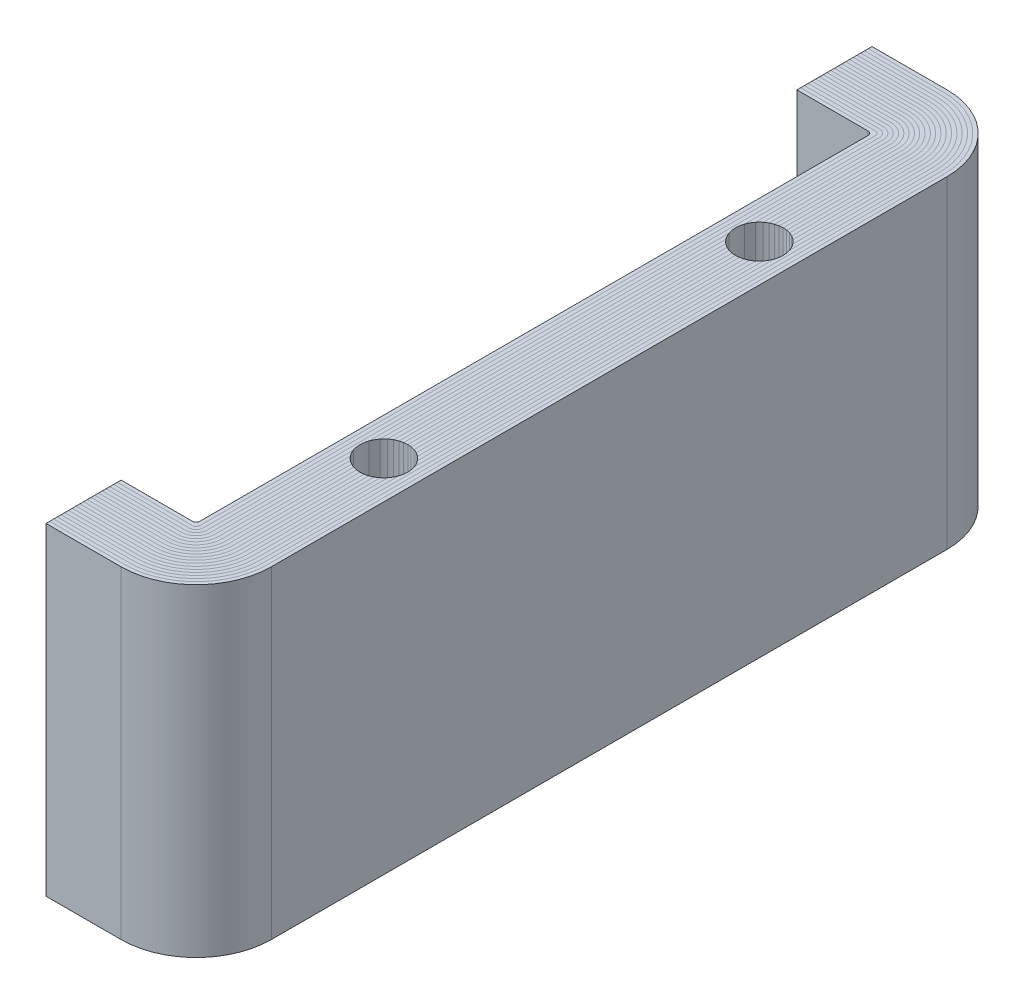
SolidWorks part; units mm, degrees
other "Item de detalhe1"
other "Pasta de soldas"
other "Cordão de solda...1"
material "AISI 304"
ref_plane "Plano frontal" through (0, 0, 0) normal (0, 0, 1) x (1, 0, 0)
ref_plane "Plano superior" through (0, 0, 0) normal (0, 1, 0) x (1, 0, 0)
ref_plane "Plano direito" through (0, 0, 0) normal (1, 0, 0) x (0, 0, -1)
sketch "Esboço2" plane through (0, 0, 0) normal (1, 0, 0) x (0, 0, -1)
  line L13 (0, 0) -> (-110, 0)
  line L14 (0, 0) -> (0, 43)
  line L15 (0, 43) -> (-110, 43)
  line L16 (-110, 0) -> (-110, 43)
  dimension "D1" = 110
  dimension "D2" = 43
extrude "Ressalto-extrusão7" add sketch "Esboço2" along normal blind 0.5 contours L14 L13 L16 L15
sketch "Esboço18" plane through (0, 0, 0) normal (-1, 0, 0) x (0, 0, 1)
  line L0 (0, 43) -> (110, 43) construction
  line L1 (10, 43) -> (0, 43)
  line L2 (10, 43) -> (10, 0)
  line L3 (10, 0) -> (0, 0)
  line L4 (0, 43) -> (0, 0)
  line L6 (100, 43) -> (110, 43)
  line L7 (100, 43) -> (100, 0)
  line L8 (100, 0) -> (110, 0)
  line L9 (110, 43) -> (110, 0)
  dimension "D1" = 10
extrude "Ressalto-extrusão8" add sketch "Esboço18" along normal blind 19.5
sketch "Esboço29" plane through (0, 43, 0) normal (0, 1, 0) x (1, 0, 0)
  line L0 (-19.5, -100) -> (0, -100) construction
  line L1 (0.5, 0) -> (0.5, -110) construction
  line L2 (-9.5, -110) -> (0.5, -110)
  line L3 (0.5, -110) -> (0.5, -100)
  line L4 (-19.5, -10) -> (0, -10) construction
  line L5 (0.5, -10) -> (0.5, 0)
  line L6 (0.5, 0) -> (-9.5, 0)
  arc A0 (0.5, -100) -> (-9.5, -110) centre (-9.5, -100) cw
  arc A1 (0.5, -10) -> (-9.5, 0) centre (-9.5, -10) ccw
extrude "Corte-extrusão6" cut sketch "Esboço29" against normal through all
sketch "Esboço30" plane through (0, 43, 0) normal (0, 1, 0) x (1, 0, 0)
  line L0 (-19.5, -100) -> (0, -100) construction
  line L1 (-9.5, -109.5) -> (-19.5, -109.5)
  line L2 (-19.5, -110) -> (-19.5, -100) construction
  line L3 (-19.5, -109.5) -> (-19.5, -100)
  line L4 (-19.5, -100) -> (0, -100)
  line L5 (-19.5, -10) -> (0, -10) construction
  line L6 (-9.5, -0.5) -> (-19.5, -0.5)
  line L7 (-19.5, -10) -> (-19.5, 0) construction
  line L8 (0, -10) -> (-19.5, -10)
  line L9 (-19.5, -10) -> (-19.5, -0.5)
  arc A0 (0, -100) -> (-9.5, -109.5) centre (-9.5, -100) cw
  arc A1 (0, -10) -> (-9.5, -0.5) centre (-9.5, -10) ccw
extrude "Corte-extrusão7" cut sketch "Esboço30" against normal through all
sketch "Esboço31" plane through (0, 43, 0) normal (0, 1, 0) x (1, 0, 0)
  line L0 (-9.5, -109.5) -> (-19.5, -109.5)
  line L1 (-19.5, -109.5) -> (-19.5, -109)
  line L2 (-19.5, -109) -> (-9.5, -109)
  line L3 (-9.5, -1) -> (-19.5, -1)
  line L4 (-19.5, -1) -> (-19.5, -0.5)
  line L5 (-19.5, -0.5) -> (-9.5, -0.5)
  line L6 (-0.5, -10) -> (-0.5, -100)
  line L7 (0, -100) -> (0, -10)
  arc A0 (0, -100) -> (-9.5, -109.5) centre (-9.5, -100) cw
  arc A1 (-9.5, -109.5) -> (0, -100) centre (-9.5, -100) ccw construction
  arc A2 (-0.5, -100) -> (-9.5, -109) centre (-9.5, -100) cw
  arc A3 (-9.5, -0.5) -> (0, -10) centre (-9.5, -10) cw
  arc A4 (0, -10) -> (-9.5, -0.5) centre (-9.5, -10) ccw construction
  arc A5 (-9.5, -1) -> (-0.5, -10) centre (-9.5, -10) cw
extrude "Ressalto-extrusão20" add sketch "Esboço31" against normal blind 43 separate body
sketch "Esboço32" plane through (0, 43, 0) normal (0, 1, 0) x (1, 0, 0)
  line L0 (-0.5, -10) -> (-0.5, -100) construction
  line L1 (-9.5, -1.5) -> (-19.5, -1.5)
  line L2 (-19.5, -1.5) -> (-19.5, -1)
  line L3 (-19.5, -1) -> (-9.5, -1)
  line L4 (-0.5, -10) -> (-0.5, -100)
  line L5 (-9.5, -109) -> (-19.5, -109)
  line L6 (-19.5, -109) -> (-19.5, -108.5)
  line L7 (-19.5, -108.5) -> (-9.5, -108.5)
  line L8 (-1, -100) -> (-1, -10)
  arc A0 (-0.5, -100) -> (-9.5, -109) centre (-9.5, -100) cw
  arc A1 (-9.5, -109) -> (-0.5, -100) centre (-9.5, -100) ccw construction
  arc A2 (-1, -100) -> (-9.5, -108.5) centre (-9.5, -100) cw
  arc A3 (-9.5, -1) -> (-0.5, -10) centre (-9.5, -10) cw
  arc A4 (-9.5, -1.5) -> (-1, -10) centre (-9.5, -10) cw
extrude "Ressalto-extrusão21" add sketch "Esboço32" against normal blind 43 separate body
sketch "Esboço33" plane through (0, 43, 0) normal (0, 1, 0) x (1, 0, 0)
  line L0 (-9.5, -1.5) -> (-19.5, -1.5)
  line L1 (-19.5, -1.5) -> (-19.5, -2)
  line L2 (-19.5, -2) -> (-9.5, -2)
  line L3 (-1, -10) -> (-1, -100)
  line L4 (-1.5, -100) -> (-1.5, -10)
  line L5 (-9.5, -108.5) -> (-19.5, -108.5)
  line L6 (-19.5, -108.5) -> (-19.5, -108)
  line L7 (-19.5, -108) -> (-9.5, -108)
  arc A0 (-9.5, -108.5) -> (-1, -100) centre (-9.5, -100) ccw
  arc A1 (-9.5, -108.5) -> (-1, -100) centre (-9.5, -100) ccw construction
  arc A2 (-1.5, -100) -> (-9.5, -108) centre (-9.5, -100) cw
  arc A3 (-1, -10) -> (-9.5, -1.5) centre (-9.5, -10) ccw
  arc A4 (-1, -10) -> (-9.5, -1.5) centre (-9.5, -10) ccw construction
  arc A5 (-1.5, -10) -> (-9.5, -2) centre (-9.5, -10) ccw
extrude "Ressalto-extrusão22" add sketch "Esboço33" against normal blind 43 separate body
sketch "Esboço34" plane through (0, 43, 0) normal (0, 1, 0) x (1, 0, 0)
  line L0 (-9.5, -108) -> (-19.5, -108)
  line L1 (-19.5, -108) -> (-19.5, -107.5)
  line L2 (-19.5, -107.5) -> (-9.5, -107.5)
  line L3 (-9.5, -2) -> (-19.5, -2)
  line L4 (-19.5, -2) -> (-19.5, -2.5)
  line L5 (-19.5, -2.5) -> (-9.5, -2.5)
  line L6 (-1.5, -10) -> (-1.5, -100)
  line L7 (-2, -100) -> (-2, -10)
  arc A0 (-9.5, -108) -> (-1.5, -100) centre (-9.5, -100) ccw
  arc A1 (-9.5, -108) -> (-1.5, -100) centre (-9.5, -100) ccw construction
  arc A2 (-9.5, -107.5) -> (-2, -100) centre (-9.5, -100) ccw
  arc A3 (-9.5, -2) -> (-1.5, -10) centre (-9.5, -10) cw
  arc A4 (-1.5, -10) -> (-9.5, -2) centre (-9.5, -10) ccw construction
  arc A5 (-2, -10) -> (-9.5, -2.5) centre (-9.5, -10) ccw
extrude "Ressalto-extrusão23" add sketch "Esboço34" against normal blind 43 separate body
sketch "Esboço35" plane through (0, 43, 0) normal (0, 1, 0) x (1, 0, 0)
  line L0 (-9.5, -107.5) -> (-19.5, -107.5) construction
  line L1 (-9.5, -107.5) -> (-19.5, -107.5)
  line L2 (-19.5, -107.5) -> (-19.5, -107)
  line L3 (-9.5, -107) -> (-19.5, -107)
  line L5 (-9.5, -2.5) -> (-19.5, -2.5)
  line L6 (-19.5, -2.5) -> (-19.5, -3)
  line L7 (-19.5, -3) -> (-9.5, -3)
  line L8 (-2, -10) -> (-2, -100)
  line L9 (-2.5, -100) -> (-2.5, -10)
  arc A0 (-2, -100) -> (-9.5, -107.5) centre (-9.5, -100) cw
  arc A1 (-2.5, -100) -> (-9.5, -107) centre (-9.5, -100) cw
  arc A2 (-2.5, -10) -> (-9.5, -3) centre (-9.5, -10) ccw
  arc A3 (-2, -10) -> (-9.5, -2.5) centre (-9.5, -10) ccw
  arc A4 (-2, -10) -> (-9.5, -2.5) centre (-9.5, -10) ccw construction
extrude "Ressalto-extrusão24" add sketch "Esboço35" against normal blind 43 separate body
sketch "Esboço36" plane through (0, 43, 0) normal (0, 1, 0) x (1, 0, 0)
  line L0 (-9.5, -107) -> (-19.5, -107)
  line L1 (-19.5, -107) -> (-19.5, -106.5)
  line L2 (-19.5, -106.5) -> (-9.5, -106.5)
  line L3 (-9.5, -3) -> (-19.5, -3)
  line L4 (-19.5, -3) -> (-19.5, -3.5)
  line L5 (-19.5, -3.5) -> (-9.5, -3.5)
  line L6 (-2.5, -100) -> (-2.5, -10)
  line L7 (-3, -10) -> (-3, -100)
  arc A0 (-2.5, -100) -> (-9.5, -107) centre (-9.5, -100) cw
  arc A1 (-9.5, -107) -> (-2.5, -100) centre (-9.5, -100) ccw construction
  arc A2 (-3, -100) -> (-9.5, -106.5) centre (-9.5, -100) cw
  arc A3 (-2.5, -10) -> (-9.5, -3) centre (-9.5, -10) ccw
  arc A4 (-2.5, -10) -> (-9.5, -3) centre (-9.5, -10) ccw construction
  arc A5 (-3, -10) -> (-9.5, -3.5) centre (-9.5, -10) ccw
extrude "Ressalto-extrusão25" add sketch "Esboço36" against normal blind 43 separate body
sketch "Esboço38" plane through (0, 43, 0) normal (0, 1, 0) x (1, 0, 0)
  line L0 (-9.5, -106.5) -> (-19.5, -106.5)
  line L1 (-19.5, -106.5) -> (-19.5, -106)
  line L2 (-19.5, -106) -> (-9.5, -106)
  line L3 (-9.5, -3.5) -> (-19.5, -3.5)
  line L4 (-19.5, -3.5) -> (-19.5, -4)
  line L5 (-19.5, -4) -> (-9.5, -4)
  line L6 (-3, -100) -> (-3, -10)
  line L7 (-3.5, -10) -> (-3.5, -100)
  line L8 (-19.5, -3.5) -> (-9.5, -3.5) construction
  arc A0 (-9.5, -106.5) -> (-3, -100) centre (-9.5, -100) ccw
  arc A1 (-9.5, -106.5) -> (-3, -100) centre (-9.5, -100) ccw construction
  arc A2 (-3.5, -100) -> (-9.5, -106) centre (-9.5, -100) cw
  arc A3 (-3, -10) -> (-9.5, -3.5) centre (-9.5, -10) ccw
  arc A4 (-3, -10) -> (-9.5, -3.5) centre (-9.5, -10) ccw construction
  arc A5 (-3.5, -10) -> (-9.5, -4) centre (-9.5, -10) ccw
  point P23 (-9.2386, -4.0057)
  point P27 (-9.5, -3.5)
  point P30 (0, 0)
extrude "Ressalto-extrusão26" add sketch "Esboço38" against normal blind 43 separate body
sketch "Esboço39" plane through (0, 43, 0) normal (0, 1, 0) x (1, 0, 0)
  line L0 (-9.5, -106) -> (-19.5, -106)
  line L1 (-19.5, -106) -> (-19.5, -105.5)
  line L2 (-19.5, -105.5) -> (-9.5, -105.5)
  line L3 (-9.5, -4.5) -> (-19.5, -4.5)
  line L4 (-19.5, -4.5) -> (-19.5, -4)
  line L5 (-19.5, -4) -> (-9.5, -4)
  line L6 (-3.5, -100) -> (-3.5, -10)
  line L7 (-4, -10) -> (-4, -100)
  arc A0 (-9.5, -106) -> (-3.5, -100) centre (-9.5, -100) ccw
  arc A1 (-9.5, -106) -> (-3.5, -100) centre (-9.5, -100) ccw construction
  arc A2 (-9.5, -105.5) -> (-4, -100) centre (-9.5, -100) ccw
  arc A3 (-3.5, -10) -> (-9.5, -4) centre (-9.5, -10) ccw
  arc A4 (-3.5, -10) -> (-9.5, -4) centre (-9.5, -10) ccw construction
  arc A5 (-4, -10) -> (-9.5, -4.5) centre (-9.5, -10) ccw
extrude "Ressalto-extrusão27" add sketch "Esboço39" against normal blind 43 separate body
sketch "Esboço40" plane through (0, 43, 0) normal (0, 1, 0) x (1, 0, 0)
  line L0 (-9.5, -105.5) -> (-19.5, -105.5)
  line L1 (-19.5, -105.5) -> (-19.5, -105)
  line L2 (-19.5, -105) -> (-9.5, -105)
  line L3 (-4, -100) -> (-4, -10)
  line L4 (-4.5, -100) -> (-4.5, -10)
  line L5 (-9.5, -5) -> (-19.5, -5)
  line L6 (-19.5, -5) -> (-19.5, -4.5)
  line L7 (-19.5, -4.5) -> (-9.5, -4.5)
  arc A0 (-4, -100) -> (-9.5, -105.5) centre (-9.5, -100) cw
  arc A1 (-9.5, -105.5) -> (-4, -100) centre (-9.5, -100) ccw construction
  arc A2 (-4.5, -100) -> (-9.5, -105) centre (-9.5, -100) cw
  arc A3 (-4, -10) -> (-9.5, -4.5) centre (-9.5, -10) ccw
  arc A4 (-4, -10) -> (-9.5, -4.5) centre (-9.5, -10) ccw construction
  arc A5 (-4.5, -10) -> (-9.5, -5) centre (-9.5, -10) ccw
extrude "Ressalto-extrusão28" add sketch "Esboço40" against normal blind 43 separate body
sketch "Esboço41" plane through (0, 43, 0) normal (0, 1, 0) x (1, 0, 0)
  line L0 (-9.5, -105) -> (-19.5, -105)
  line L1 (-9.5, -105) -> (-19.5, -105) construction
  line L2 (-19.5, -105) -> (-19.5, -104.5)
  line L3 (-19.5, -104.5) -> (-9.5, -104.5)
  line L4 (-4.5, -100) -> (-4.5, -10)
  line L5 (-5, -100) -> (-5, -10)
  line L6 (-9.5, -5.5) -> (-19.5, -5.5)
  line L7 (-19.5, -5.5) -> (-19.5, -5)
  line L8 (-19.5, -5) -> (-9.5, -5)
  arc A0 (-9.5, -105) -> (-4.5, -100) centre (-9.5, -100) ccw
  arc A1 (-9.5, -105) -> (-4.5, -100) centre (-9.5, -100) ccw construction
  arc A2 (-9.5, -104.5) -> (-5, -100) centre (-9.5, -100) ccw
  arc A3 (-4.5, -10) -> (-9.5, -5) centre (-9.5, -10) ccw
  arc A4 (-4.5, -10) -> (-9.5, -5) centre (-9.5, -10) ccw construction
  arc A5 (-5, -10) -> (-9.5, -5.5) centre (-9.5, -10) ccw
extrude "Ressalto-extrusão29" add sketch "Esboço41" against normal blind 43 separate body
sketch "Esboço42" plane through (0, 43, 0) normal (0, 1, 0) x (1, 0, 0)
  line L0 (-9.5, -104.5) -> (-19.5, -104.5)
  line L1 (-19.5, -104.5) -> (-19.5, -104)
  line L2 (-19.5, -104) -> (-9.5, -104)
  line L3 (-5, -100) -> (-5, -10)
  line L4 (-5.5, -100) -> (-5.5, -10)
  line L5 (-9.5, -6) -> (-19.5, -6)
  line L6 (-19.5, -6) -> (-19.5, -5.5)
  line L7 (-19.5, -5.5) -> (-9.5, -5.5)
  arc A0 (-9.5, -104.5) -> (-5, -100) centre (-9.5, -100) ccw
  arc A1 (-9.5, -104.5) -> (-5, -100) centre (-9.5, -100) ccw construction
  arc A2 (-9.5, -104) -> (-5.5, -100) centre (-9.5, -100) ccw
  arc A3 (-5, -10) -> (-9.5, -5.5) centre (-9.5, -10) ccw
  arc A4 (-5, -10) -> (-9.5, -5.5) centre (-9.5, -10) ccw construction
  arc A5 (-5.5, -10) -> (-9.5, -6) centre (-9.5, -10) ccw
extrude "Ressalto-extrusão30" add sketch "Esboço42" against normal blind 43 separate body
sketch "Esboço43" plane through (0, 43, 0) normal (0, 1, 0) x (1, 0, 0)
  line L0 (-9.5, -104) -> (-19.5, -104) construction
  line L1 (-9.5, -104) -> (-19.5, -104)
  line L2 (-19.5, -104) -> (-19.5, -103.5)
  line L3 (-19.5, -103.5) -> (-9.5, -103.5)
  line L4 (-5.5, -100) -> (-5.5, -10)
  line L5 (-6, -100) -> (-6, -10)
  line L6 (-9.5, -6.5) -> (-19.5, -6.5)
  line L7 (-19.5, -6.5) -> (-19.5, -6)
  line L8 (-19.5, -6) -> (-9.5, -6)
  arc A0 (-5.5, -100) -> (-9.5, -104) centre (-9.5, -100) cw
  arc A1 (-6, -100) -> (-9.5, -103.5) centre (-9.5, -100) cw
  arc A2 (-5.5, -10) -> (-9.5, -6) centre (-9.5, -10) ccw
  arc A3 (-5.5, -10) -> (-9.5, -6) centre (-9.5, -10) ccw construction
  arc A4 (-6, -10) -> (-9.5, -6.5) centre (-9.5, -10) ccw
extrude "Ressalto-extrusão31" add sketch "Esboço43" against normal blind 43 separate body
sketch "Esboço44" plane through (0, 43, 0) normal (0, 1, 0) x (1, 0, 0)
  line L0 (-9.5, -103.5) -> (-19.5, -103.5)
  line L1 (-19.5, -103.5) -> (-19.5, -103)
  line L2 (-19.5, -103) -> (-9.5, -103)
  line L3 (-6, -100) -> (-6, -10)
  line L4 (-6, -10) -> (-6, -100) construction
  line L5 (-6.5, -100) -> (-6.5, -10)
  line L6 (-9.5, -7) -> (-19.5, -7)
  line L7 (-19.5, -7) -> (-19.5, -6.5)
  line L8 (-19.5, -6) -> (-19.5, -6.5) construction
  line L9 (-19.5, -6.5) -> (-9.5, -6.5) construction
  line L10 (-19.5, -6.5) -> (-9.5, -6.5)
  arc A0 (-9.5, -103.5) -> (-6, -100) centre (-9.5, -100) ccw
  arc A1 (-9.5, -103.5) -> (-6, -100) centre (-9.5, -100) ccw construction
  arc A2 (-9.5, -103) -> (-6.5, -100) centre (-9.5, -100) ccw
  arc A3 (-6, -10) -> (-9.5, -6.5) centre (-9.5, -10) ccw construction
  arc A4 (-9.5, -6.5) -> (-6, -10) centre (-9.5, -10) cw
  arc A5 (-6.5, -10) -> (-9.5, -7) centre (-9.5, -10) ccw
extrude "Ressalto-extrusão32" add sketch "Esboço44" against normal blind 43 separate body
sketch "Esboço45" plane through (0, 43, 0) normal (0, 1, 0) x (1, 0, 0)
  line L0 (-9.5, -103) -> (-19.5, -103)
  line L1 (-19.5, -103) -> (-19.5, -102.5)
  line L2 (-19.5, -102.5) -> (-9.5, -102.5)
  line L3 (-6.5, -100) -> (-6.5, -10)
  line L4 (-7, -100) -> (-7, -10)
  line L5 (-9.5, -7.5) -> (-19.5, -7.5)
  line L6 (-19.5, -7.5) -> (-19.5, -7)
  line L7 (-19.5, -7) -> (-9.5, -7)
  arc A0 (-6.5, -100) -> (-9.5, -103) centre (-9.5, -100) cw
  arc A1 (-9.5, -103) -> (-6.5, -100) centre (-9.5, -100) ccw construction
  arc A2 (-7, -100) -> (-9.5, -102.5) centre (-9.5, -100) cw
  arc A3 (-6.5, -10) -> (-9.5, -7) centre (-9.5, -10) ccw
  arc A4 (-6.5, -10) -> (-9.5, -7) centre (-9.5, -10) ccw construction
  arc A5 (-7, -10) -> (-9.5, -7.5) centre (-9.5, -10) ccw
extrude "Ressalto-extrusão33" add sketch "Esboço45" against normal blind 43 separate body
sketch "Esboço46" plane through (0, 43, 0) normal (0, 1, 0) x (1, 0, 0)
  line L0 (-9.5, -102.5) -> (-19.5, -102.5)
  line L1 (-19.5, -102.5) -> (-19.5, -102)
  line L2 (-19.5, -102) -> (-9.5, -102)
  line L3 (-7, -100) -> (-7, -10)
  line L4 (-7, -10) -> (-7, -100) construction
  line L5 (-7.5, -100) -> (-7.5, -10)
  line L6 (-9.5, -7.5) -> (-19.5, -7.5)
  line L7 (-19.5, -7.5) -> (-19.5, -8)
  line L8 (-19.5, -8) -> (-9.5, -8)
  arc A0 (-7, -100) -> (-9.5, -102.5) centre (-9.5, -100) cw
  arc A1 (-9.5, -102.5) -> (-7, -100) centre (-9.5, -100) ccw construction
  arc A2 (-7.5, -100) -> (-9.5, -102) centre (-9.5, -100) cw
  arc A3 (-7, -10) -> (-9.5, -7.5) centre (-9.5, -10) ccw construction
  arc A4 (-7, -10) -> (-9.5, -7.5) centre (-9.5, -10) ccw
  arc A5 (-7.5, -10) -> (-9.5, -8) centre (-9.5, -10) ccw
extrude "Ressalto-extrusão34" add sketch "Esboço46" against normal blind 43 separate body
sketch "Esboço47" plane through (0, 43, 0) normal (0, 1, 0) x (1, 0, 0)
  line L0 (-9.5, -102) -> (-19.5, -102)
  line L1 (-19.5, -102) -> (-19.5, -101.5)
  line L2 (-19.5, -101.5) -> (-9.5, -101.5)
  line L3 (-7.5, -100) -> (-7.5, -10)
  line L4 (-8, -100) -> (-8, -10)
  line L5 (-9.5, -8) -> (-19.5, -8)
  line L6 (-19.5, -8) -> (-19.5, -8.5)
  line L7 (-19.5, -8.5) -> (-9.5, -8.5)
  arc A0 (-7.5, -100) -> (-9.5, -102) centre (-9.5, -100) cw
  arc A1 (-9.5, -102) -> (-7.5, -100) centre (-9.5, -100) ccw construction
  arc A3 (-8, -100) -> (-9.5, -101.5) centre (-9.5, -100) cw
  arc A4 (-7.5, -10) -> (-9.5, -8) centre (-9.5, -10) ccw
  arc A5 (-7.5, -10) -> (-9.5, -8) centre (-9.5, -10) ccw construction
  arc A6 (-8, -10) -> (-9.5, -8.5) centre (-9.5, -10) ccw
extrude "Ressalto-extrusão35" add sketch "Esboço47" against normal blind 43 separate body
sketch "Esboço48" plane through (0, 43, 0) normal (0, 1, 0) x (1, 0, 0)
  line L0 (-9.5, -101.5) -> (-19.5, -101.5)
  line L1 (-19.5, -101.5) -> (-19.5, -101)
  line L2 (-19.5, -101) -> (-9.5, -101)
  line L3 (-8, -100) -> (-8, -10)
  line L4 (-8.5, -100) -> (-8.5, -10)
  line L5 (-9.5, -8.5) -> (-19.5, -8.5)
  line L6 (-19.5, -8.5) -> (-19.5, -9)
  line L7 (-19.5, -9) -> (-9.5, -9)
  arc A0 (-8, -100) -> (-9.5, -101.5) centre (-9.5, -100) cw
  arc A2 (-9.5, -101.5) -> (-8, -100) centre (-9.5, -100) ccw construction
  arc A3 (-8.5, -100) -> (-9.5, -101) centre (-9.5, -100) cw
  arc A4 (-8, -10) -> (-9.5, -8.5) centre (-9.5, -10) ccw construction
  arc A5 (-8, -10) -> (-9.5, -8.5) centre (-9.5, -10) ccw
  arc A6 (-8.5, -10) -> (-9.5, -9) centre (-9.5, -10) ccw
extrude "Ressalto-extrusão37" add sketch "Esboço48" against normal blind 43 separate body
sketch "Esboço49" plane through (0, 43, 0) normal (0, 1, 0) x (1, 0, 0)
  line L0 (-9.5, -101) -> (-19.5, -101)
  line L1 (-19.5, -101) -> (-19.5, -100.5)
  line L2 (-19.5, -100.5) -> (-9.5, -100.5)
  line L3 (-8.5, -100) -> (-8.5, -10)
  line L4 (-8.5, -10) -> (-8.5, -100) construction
  line L5 (-9, -100) -> (-9, -10)
  line L6 (-9.5, -9.5) -> (-19.5, -9.5)
  line L7 (-19.5, -9.5) -> (-19.5, -9)
  line L8 (-19.5, -9) -> (-9.5, -9)
  line L9 (-19.5, -9) -> (-9.5, -9) construction
  arc A0 (-8.5, -100) -> (-9.5, -101) centre (-9.5, -100) cw
  arc A1 (-9.5, -101) -> (-8.5, -100) centre (-9.5, -100) ccw construction
  arc A2 (-9, -100) -> (-9.5, -100.5) centre (-9.5, -100) cw
  arc A3 (-8.5, -10) -> (-9.5, -9) centre (-9.5, -10) ccw construction
  arc A4 (-9, -10) -> (-9.5, -9.5) centre (-9.5, -10) ccw
  arc A5 (-9.5, -9) -> (-8.5, -10) centre (-9.5, -10) cw
  point P30 (0, 0)
extrude "Ressalto-extrusão38" add sketch "Esboço49" against normal blind 43 separate body
sketch "Esboço50" plane through (0, 43, 0) normal (0, 1, 0) x (1, 0, 0)
  line L0 (-9.5, -100.5) -> (-19.5, -100.5)
  line L1 (-19.5, -100.5) -> (-19.5, -100)
  line L2 (-19.5, -100) -> (-10, -100)
  line L3 (-9, -100) -> (-9, -10)
  line L4 (-9.5, -99.5) -> (-9.5, -10.5)
  line L5 (-10, -10) -> (-19.5, -10)
  line L6 (-19.5, -10) -> (-19.5, -9.5)
  line L7 (-19.5, -9.5) -> (-9.5, -9.5)
  line L8 (-19.5, -9.5) -> (-9.5, -9.5) construction
  arc A0 (-9, -100) -> (-9.5, -100.5) centre (-9.5, -100) cw
  arc A1 (-10, -100) -> (-9.5, -99.5) centre (-10, -99.5) ccw
  arc A2 (-9, -10) -> (-9.5, -9.5) centre (-9.5, -10) ccw
  arc A3 (-9.5, -10.5) -> (-10, -10) centre (-10, -10.5) ccw
  arc A4 (-9, -10) -> (-9.5, -9.5) centre (-9.5, -10) ccw construction
  dimension "D1" = 0.5
  dimension "D2" = 0.5
  dimension "D4" = 0.5
extrude "Ressalto-extrusão39" add sketch "Esboço50" against normal blind 43 separate body
hole_wizard "Broca de rosquear para tarraxa de M3x0.51" positions "Esboço51" profile "Esboço52" hole size "M3x0.5" standard "Ansi Metric"
sketch "Esboço51" plane through (0, 43, 0) normal (0, 1, 0) x (1, 0, 0)
  line L0 (-9.5, -10.5) -> (-9.5, -99.5) construction
  line L1 (-9.5, -110) -> (-19.5, -110) construction
  line L2 (-9.5, 0) -> (-19.5, 0) construction
  point P12 (-4.5, -80)
  point P14 (-4.5, -30)
  point P21 (-4.5, -75.8538)
  dimension "D1" = 5
  dimension "D2" = 5
  dimension "D3" = 30
  dimension "D4" = 30
sketch "Esboço52" plane through (-4.5, 43, 80) normal (1, 0, 0) x (0, 0, 1)
  line L0 (0, 0) -> (0, 23.49)
  line L1 (0, 23.49) -> (3.175, 21.5823)
  line L2 (3.175, 21.5823) -> (3.175, 0)
  line L5 (3.175, 0) -> (0, 0)
  line L10 (0, 23.49) -> (-3.175, 21.5823) construction
  line L11 (0, -6.35) -> (0, 107.95) construction
  dimension "Hole Dia." = 6.35
  dimension "Hole Depth" = 23.49
  dimension "Drill Angle" = 118
sketch "Curva-Linhas1" plane through (0, 0, 0) normal (0, 1, 0) x (1, 0, 0)
sketch "Caixa delimitadora1" plane through (0, 0, 0) normal (0, 1, 0) x (1, 0, 0)
